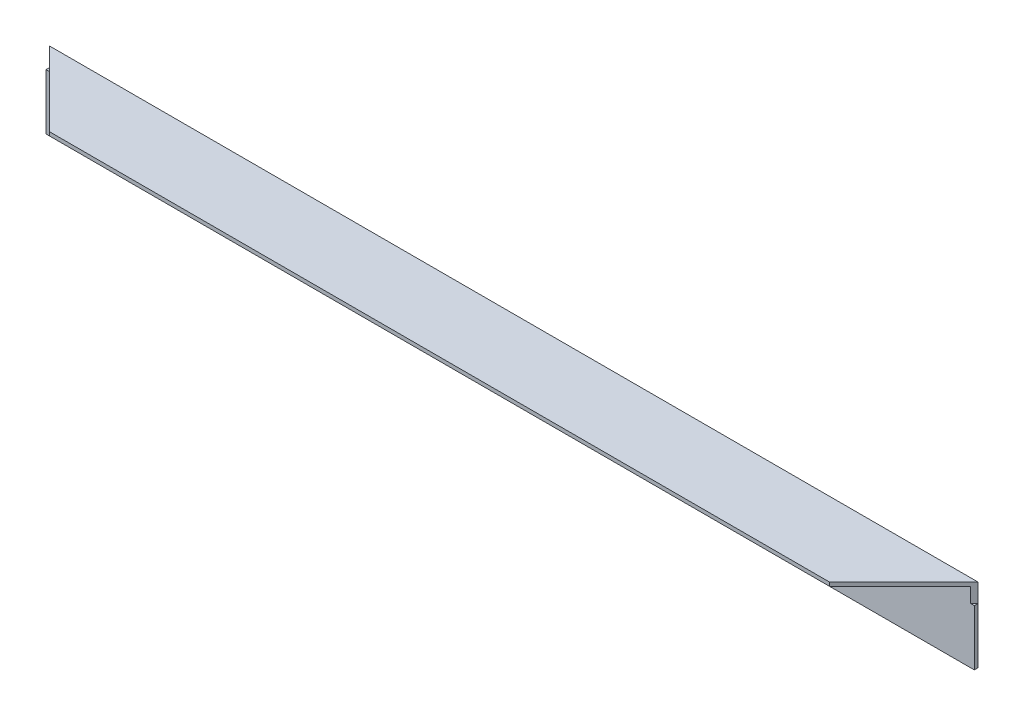
SolidWorks part; units mm, degrees
material "1060 Alloy"
ref_plane "Front Plane" through (0, 0, 0) normal (0, 0, 1) x (1, 0, 0)
ref_plane "Top Plane" through (0, 0, 0) normal (0, 1, 0) x (1, 0, 0)
ref_plane "Right Plane" through (0, 0, 0) normal (1, 0, 0) x (0, 0, -1)
sketch "Sketch2" plane through (0, 0, 0) normal (0, 0, 1) x (1, 0, 0)
  line L1 (-329.5455, 93.2765) -> (170.4545, 93.2765)
  line L2 (-329.5455, 93.2765) -> (-329.5455, 53.2765)
  line L3 (-329.5455, 53.2765) -> (170.4545, 53.2765)
  line L4 (170.4545, 93.2765) -> (170.4545, 53.2765)
  dimension "D1" = 500
  dimension "D2" = 40
extrude "Boss-Extrude1" add sketch "Sketch2" along normal blind 40
sketch "Sketch3" plane through (-329.5455, 0, 0) normal (-1, 0, 0) x (0, 0, 1)
  line L0 (40, 93.2765) -> (40, 53.2765) construction
  line L1 (2, 91.2765) -> (40, 91.2765)
  line L2 (2, 91.2765) -> (2, 53.2765)
  line L3 (2, 53.2765) -> (40, 53.2765)
  line L4 (40, 91.2765) -> (40, 53.2765)
  line L5 (40, 53.2765) -> (0, 53.2765) construction
  line L6 (0, 93.2765) -> (0, 53.2765) construction
  line L7 (40, 93.2765) -> (0, 93.2765) construction
  dimension "D1" = 0
  dimension "D2" = 0
  dimension "D3" = 2
  dimension "D4" = 2
extrude "Cut-Extrude1" cut sketch "Sketch3" against normal up to surface (500 mm away) up to face at (170.4545, 73.2765, 20)
sketch "Sketch4" plane through (0, 93.2765, 0) normal (0, 1, 0) x (1, 0, 0)
  line L0 (-329.5455, 0) -> (-329.5455, -40)
  line L1 (-329.5455, -40) -> (-289.5455, -40)
  line L2 (170.4545, -40) -> (-329.5455, -40) construction
  line L3 (-289.5455, -40) -> (-329.5455, 0)
  line L4 (170.4545, -40) -> (170.4545, 0)
  line L5 (170.4545, 0) -> (130.4545, -40)
  line L6 (130.4545, -40) -> (170.4545, -40)
  dimension "D1" = 40
  dimension "D2" = 40
extrude "Cut-Extrude2" cut sketch "Sketch4" against normal blind 10
